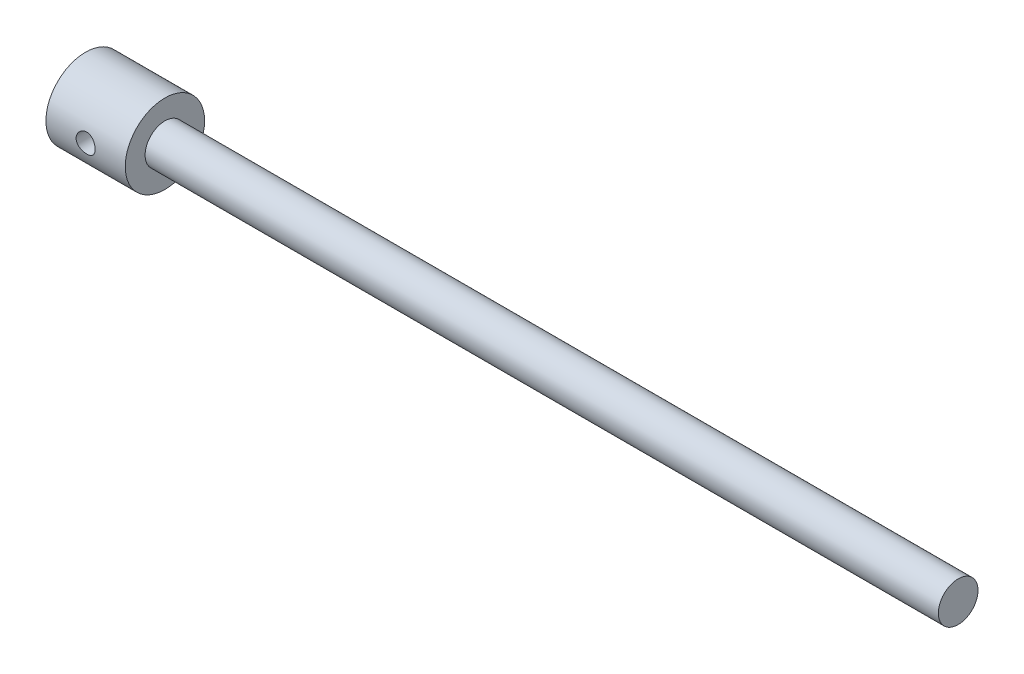
SolidWorks part; units mm, degrees
ref_plane "Płaszczyzna przednia" through (0, 0, 0) normal (0, 0, 1) x (1, 0, 0)
ref_plane "Płaszczyzna górna" through (0, 0, 0) normal (0, 1, 0) x (1, 0, 0)
ref_plane "Płaszczyzna prawa" through (0, 0, 0) normal (1, 0, 0) x (0, 0, -1)
sketch "Szkic1" plane through (0, 0, 0) normal (1, 0, 0) x (0, 0, -1)
  circle A0 centre (0, 0) radius 25
  dimension "D1" = 50
extrude "Dodanie-wyciągnięcie1" add sketch "Szkic1" along normal blind 50
sketch "Szkic2" plane through (0, 0, 0) normal (0, 0, 1) x (1, 0, 0)
  circle A0 centre (25, 0) radius 6
  point P2 (0, 0)
  dimension "D1" = 12
  dimension "D2" = 25
extrude "Wytnij-wyciągnięcie2" cut sketch "Szkic2" against normal mid plane 90
sketch "Szkic3" plane through (50, 0, 0) normal (1, 0, 0) x (0, 0, -1)
  circle A0 centre (0, 0) radius 12.5
  dimension "D1" = 25
extrude "Dodanie-wyciągnięcie2" add sketch "Szkic3" along normal blind 500
cosmetic thread "Oznaczenie gwintu1" parameters "D1"=5, "D2"=6.619
cosmetic thread "Oznaczenie gwintu2" parameters "D1"=5, "D2"=6.619
